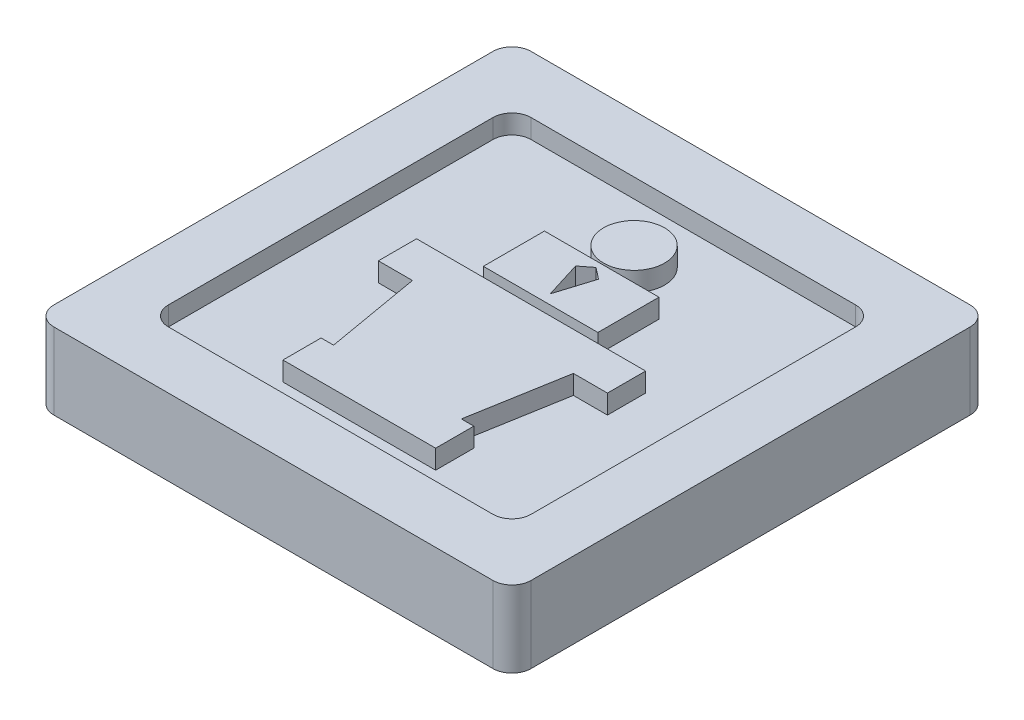
SolidWorks part; units mm, degrees
ref_plane "前视基准面" through (0, 0, 0) normal (0, 0, 1) x (1, 0, 0)
ref_plane "上视基准面" through (0, 0, 0) normal (0, 1, 0) x (1, 0, 0)
ref_plane "右视基准面" through (0, 0, 0) normal (1, 0, 0) x (0, 0, -1)
sketch "草图1" plane through (0, 0, 0) normal (0, 1, 0) x (1, 0, 0)
  line L1 (-12.5, -12.5) -> (12.5, -12.5)
  line L2 (-12.5, -12.5) -> (-12.5, 12.5)
  line L3 (-12.5, 12.5) -> (12.5, 12.5)
  line L4 (12.5, -12.5) -> (12.5, 12.5)
  line L5 (-12.5, -12.5) -> (12.5, 12.5) construction
  line L6 (-12.5, 12.5) -> (12.5, -12.5) construction
  point P0 (0, 0)
  dimension "D1" = 25
extrude "凸台-拉伸1" add sketch "草图1" along normal blind 4
sketch "草图2" plane through (0, 4, 0) normal (0, 1, 0) x (1, 0, 0)
  line L0 (9.5, -9.5) -> (9.5, 9.5)
  line L1 (9.5, 9.5) -> (-9.5, 9.5)
  line L2 (-9.5, 9.5) -> (-9.5, -9.5)
  line L3 (-9.5, -9.5) -> (9.5, -9.5)
  line L4 (12.5, -12.5) -> (12.5, 12.5)
  line L5 (12.5, 12.5) -> (-12.5, 12.5)
  line L6 (-12.5, 12.5) -> (-12.5, -12.5)
  line L7 (-12.5, -12.5) -> (12.5, -12.5)
  line L8 (12.5, -12.5) -> (12.5, 12.5)
  line L9 (12.5, 12.5) -> (-12.5, 12.5)
  line L10 (-12.5, 12.5) -> (-12.5, -12.5)
  line L11 (-12.5, -12.5) -> (12.5, -12.5)
  dimension "D1" = 0
  dimension "D2" = 3
extrude "切除-拉伸1" cut sketch "草图2" against normal blind 1 contours L2 L3 L0 L1
sketch "草图3" plane through (0, 3, 0) normal (0, 1, 0) x (1, 0, 0)
  line L0 (-4.2161, -1) -> (-3, -8)
  line L5 (6, 1) -> (-6, 1)
  line L6 (6, 1) -> (6, -1)
  line L7 (6, -1) -> (-6, -1)
  line L8 (-6, 1) -> (-6, -1)
  line L9 (6, 1) -> (-6, -1) construction
  line L10 (6, -1) -> (-6, 1) construction
  line L11 (-3, -8) -> (3, -8)
  line L12 (3, -8) -> (4.2161, -1)
  line L13 (0, -1) -> (0, -8) construction
  line L14 (-3, 1.5) -> (3, 1.5)
  line L15 (-3, 1.5) -> (-3, 4.7)
  line L16 (3, 1.5) -> (3, 4.7)
  line L17 (-3, 4.7) -> (3, 4.7)
  line L18 (0, 4.4) -> (-0.6, 3.9332)
  line L19 (-0.6, 3.9332) -> (0, 2)
  line L20 (0, 2) -> (0.6, 3.9332)
  line L21 (0.6, 3.9332) -> (0, 4.4)
  line L22 (0, 4.7) -> (0, 4.4) construction
  line L23 (0, 2) -> (0, 4.4) construction
  line L24 (0, 2) -> (0, 1.5) construction
  line L25 (-0.6, 3.9332) -> (0.6, 3.9332) construction
  line L27 (-4, -8) -> (4, -8)
  line L28 (-4, -8) -> (-4, -6)
  line L29 (-4, -6) -> (4, -6)
  line L30 (4, -8) -> (4, -6)
  line L31 (-4, -8) -> (4, -6) construction
  line L32 (-4, -6) -> (4, -8) construction
  circle A0 centre (0, 6.3943) radius 1.6
  point P0 (0, 0)
  point P23 (0, -7)
  dimension "D5" = 3.2
  dimension "D1" = 2
  dimension "D2" = 12
  dimension "D3" = 6
  dimension "D4" = 7
  dimension "D6" = 0.3
  dimension "D7" = 0.5
  dimension "D8" = 3.2
  dimension "D9" = 0.5
  dimension "D10" = 6
  dimension "D11" = 1.2
  dimension "D12" = 2
  dimension "D13" = 8
extrude "凸台-拉伸2" add sketch "草图3" along normal blind 1 contours A0 | L17 L15 L14 L16 L21 L20 L19 L18 | L5 L8 L7 L6 | L11 L12 L7 L0 | L29 L0 L11 L12 | L29 L28 L27 L0 | L27 L30 L29 L12
fillet "圆角1" radius 1 8 edges at (-9.5, 3.5, 9.5) (9.5, 3.5, 9.5) (9.5, 3.5, -9.5) (-9.5, 3.5, -9.5) (-12.5, 2, -12.5) (-12.5, 2, 12.5) (12.5, 2, 12.5) (12.5, 2, -12.5)
